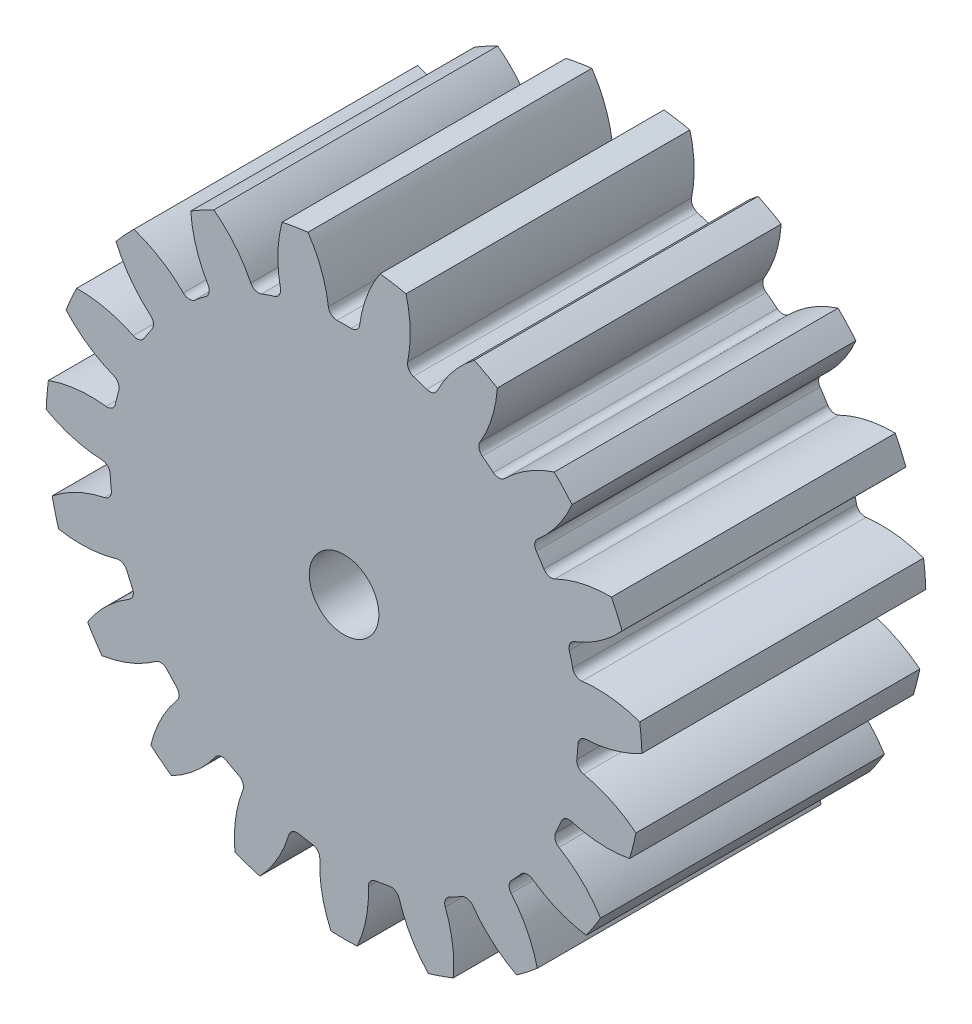
SolidWorks part; units mm, degrees
ref_plane "Front Plane" through (0, 0, 0) normal (0, 0, 1) x (1, 0, 0)
ref_plane "Top Plane" through (0, 0, 0) normal (0, 1, 0) x (1, 0, 0)
ref_plane "Right Plane" through (0, 0, 0) normal (1, 0, 0) x (0, 0, -1)
sketch "Sketch1" plane through (0, 0, 0) normal (0, 0, 1) x (1, 0, 0)
  circle A0 centre (0, 0) radius 19
  circle A1 centre (0, 0) radius 21
  circle A2 centre (0, 0) radius 16.5
  dimension "D1" = 38
  dimension "D2" = 42
  dimension "D3" = 4.5
extrude "Boss-Extrude1" add sketch "Sketch1" along normal mid plane 20 contours A1
sketch "Sketch2" plane through (0, 0, 0) normal (0, 0, 1) x (1, 0, 0)
  line L0 (0, 0) -> (0, 21) construction
  line L1 (-1.569, 18.9351) -> (1.569, 18.9351) construction
  line L2 (-1.052, 16.4664) -> (0, 0) construction
  line L3 (0, 14.6243) -> (-2.6272, 21.8426) construction
  line L4 (0, 0) -> (4.5657, 27.3609) construction
  line L5 (1.569, 18.9351) -> (4.6642, 18.4186) construction
  circle A0 centre (0, 0) radius 21 construction
  arc A1 (-3.2437, 21.7596) -> (-1.052, 16.4664) centre (-9.9058, 15.9008) cw
  arc A2 (3.2437, 21.7596) -> (1.052, 16.4664) centre (9.9058, 15.9008) ccw
  circle A3 centre (0, 0) radius 16.5 construction
  arc A4 (1.052, 16.4664) -> (-1.052, 16.4664) centre (0, 0) ccw
  circle A5 centre (0, 0) radius 19 construction
  circle A8 centre (0, 0) radius 22
  arc A9 (3.2437, 21.7596) -> (-3.2437, 21.7596) centre (0, 0) ccw
  dimension "D2" = 20
  dimension "D3" = 9.474
  dimension "D1" = 1
extrude "Cut-Extrude2" cut sketch "Sketch2" against normal through all both and the other way through all
fillet "Fillet1" radius 0.6 2 edges at (1.052, 16.4664, 0) (-1.052, 16.4664, 0)
pattern_circular "CirPattern3" count 19 over 360 about axis through (0, 0, 0) along (0, 0, 1) of "Cut-Extrude2", "Fillet1"
sketch "Sketch3" plane through (0, 0, -10) normal (0, 0, -1) x (-1, 0, 0)
  circle A0 centre (0, 0) radius 2.45
  dimension "D1" = 4.9
extrude "Cut-Extrude3" cut sketch "Sketch3" against normal through all
sketch "Sketch4" plane through (0, 0, -10) normal (0, 0, -1) x (-1, 0, 0)
  line L0 (0, 0) -> (-0.5945, 6.081) construction
  line L1 (0, 0) -> (0.5941, 6.081) construction
  line L2 (0, 0) -> (0, 5.4) construction
  arc A0 (-0.5945, 6.081) -> (-1.3137, 5.9671) centre (0, 0) ccw
  arc A1 (-0.5945, 6.081) -> (0.5945, 6.081) centre (0, 6) ccw
  arc A2 (1.3137, 5.9671) -> (2.4445, 5.5997) centre (1.8541, 5.7063) ccw
  arc A3 (3.0934, 5.2691) -> (4.0553, 4.5702) centre (3.5267, 4.8541) ccw
  arc A4 (4.5702, 4.0553) -> (5.2691, 3.0934) centre (4.8541, 3.5267) ccw
  arc A5 (5.5997, 2.4445) -> (5.9671, 1.3137) centre (5.7063, 1.8541) ccw
  arc A6 (6.081, 0.5945) -> (6.081, -0.5945) centre (6, 0) ccw
  arc A7 (5.9671, -1.3137) -> (5.5997, -2.4445) centre (5.7063, -1.8541) ccw
  arc A8 (5.2691, -3.0934) -> (4.5702, -4.0553) centre (4.8541, -3.5267) ccw
  arc A9 (4.0553, -4.5702) -> (3.0934, -5.2691) centre (3.5267, -4.8541) ccw
  arc A10 (2.4445, -5.5997) -> (1.3137, -5.9671) centre (1.8541, -5.7063) ccw
  arc A11 (0.5945, -6.081) -> (-0.5945, -6.081) centre (0, -6) ccw
  arc A12 (-1.3137, -5.9671) -> (-2.4445, -5.5997) centre (-1.8541, -5.7063) ccw
  arc A13 (-3.0934, -5.2691) -> (-4.0553, -4.5702) centre (-3.5267, -4.8541) ccw
  arc A14 (-4.5702, -4.0553) -> (-5.2691, -3.0934) centre (-4.8541, -3.5267) ccw
  arc A15 (-5.5997, -2.4445) -> (-5.9671, -1.3137) centre (-5.7063, -1.8541) ccw
  arc A16 (-6.081, -0.5945) -> (-6.081, 0.5945) centre (-6, 0) ccw
  arc A17 (-5.9671, 1.3137) -> (-5.5997, 2.4445) centre (-5.7063, 1.8541) ccw
  arc A18 (-5.2691, 3.0934) -> (-4.5702, 4.0553) centre (-4.8541, 3.5267) ccw
  arc A19 (-4.0553, 4.5702) -> (-3.0934, 5.2691) centre (-3.5267, 4.8541) ccw
  arc A20 (-2.4445, 5.5997) -> (-1.3137, 5.9671) centre (-1.8541, 5.7063) ccw
  arc A21 (1.3137, 5.9671) -> (0.5941, 6.081) centre (0, 0) ccw
  arc A22 (3.0934, 5.2691) -> (2.4445, 5.5997) centre (0, 0) ccw
  arc A23 (4.5702, 4.0553) -> (4.0553, 4.5702) centre (0, 0) ccw
  arc A24 (5.5997, 2.4445) -> (5.2691, 3.0934) centre (0, 0) ccw
  arc A25 (6.081, 0.5945) -> (5.9671, 1.3137) centre (0, 0) ccw
  arc A26 (5.9671, -1.3137) -> (6.081, -0.5945) centre (0, 0) ccw
  arc A27 (5.2691, -3.0934) -> (5.5997, -2.4445) centre (0, 0) ccw
  arc A28 (4.0553, -4.5702) -> (4.5702, -4.0553) centre (0, 0) ccw
  arc A29 (2.4445, -5.5997) -> (3.0934, -5.2691) centre (0, 0) ccw
  arc A30 (0.5945, -6.081) -> (1.3137, -5.9671) centre (0, 0) ccw
  arc A31 (-1.3137, -5.9671) -> (-0.5945, -6.081) centre (0, 0) ccw
  arc A32 (-3.0934, -5.2691) -> (-2.4445, -5.5997) centre (0, 0) ccw
  arc A33 (-4.5702, -4.0553) -> (-4.0553, -4.5702) centre (0, 0) ccw
  arc A34 (-5.5997, -2.4445) -> (-5.2691, -3.0934) centre (0, 0) ccw
  arc A35 (-5.9671, 1.3137) -> (-5.9671, -1.3137) centre (0, 0) ccw
  arc A36 (-4.0553, 4.5702) -> (-5.5997, 2.4445) centre (0, 0) ccw
  arc A37 (-2.4445, 5.5997) -> (-3.0934, 5.2691) centre (0, 0) ccw
  point P49 (0, 0)
  dimension "D1" = 12.22
  dimension "D5" = 1.2
  dimension "D2" = 20
  dimension "D3" = 5.58
extrude "Cut-Extrude4" cut sketch "Sketch4" against normal blind 11 contours A20 A37 A19 A36 A18 A17 A35 A16 A15 A34 A14 A33 A13 A32 A12 A31 A11 A30 A10 A29 A9 A28 A8 A27 A7 A26 A6 A25 A5 A24 A4 A23 A3 A22 A2 A21 A1 A0
equation "\"Module\" = 2mm"
equation "\"Number of Teeth\"= 19"
equation "\"D1@Sketch1\"=\"Module\"*\"Number of Teeth\""
equation "\"D2@Sketch1\"=(\"Number of Teeth\"+2)*\"Module\""
equation "\"D3@Sketch1\"= \"Module\"*if(\"Module\"=>1.25,2.25,2.4)"
equation "\"D3@Sketch2\"=180/\"Number of Teeth\""
equation "\"D1@CirPattern3\"=\"Number of Teeth\""
